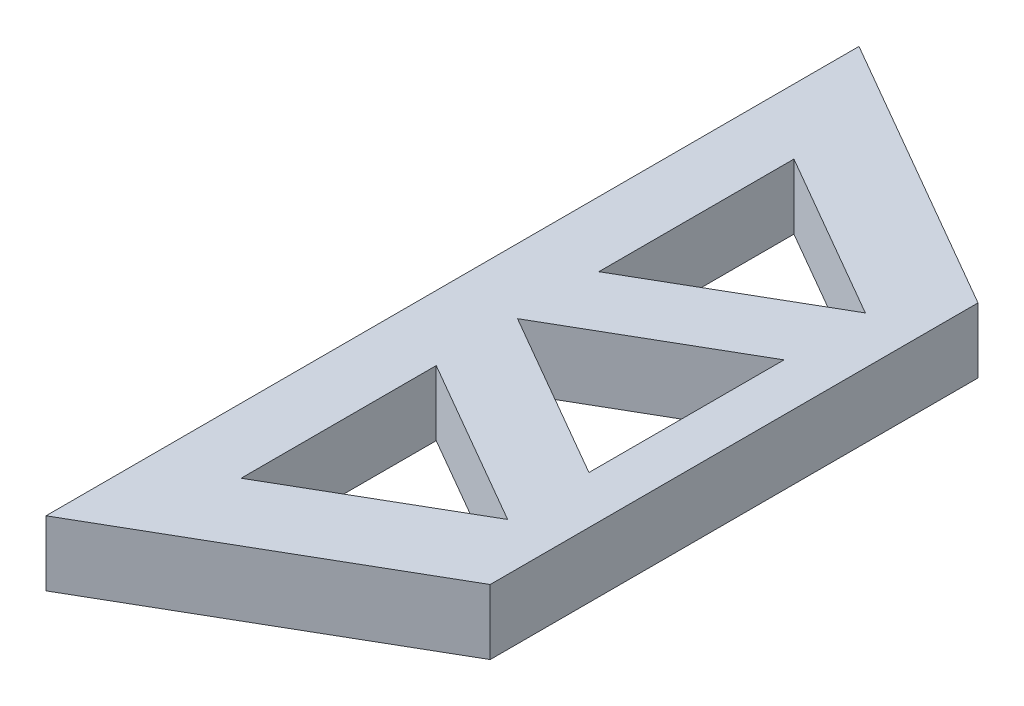
SolidWorks part; units mm, degrees
ref_plane "Front Plane" through (0, 0, 0) normal (0, 0, 1) x (1, 0, 0)
ref_plane "Top Plane" through (0, 0, 0) normal (0, 1, 0) x (1, 0, 0)
ref_plane "Right Plane" through (0, 0, 0) normal (1, 0, 0) x (0, 0, -1)
sketch "Sketch1" plane through (0, 0, 0) normal (0, 1, 0) x (1, 0, 0)
  line L0 (0, 125) -> (0, -125)
  line L1 (0, 125) -> (86.6025, 75)
  line L2 (0, -125) -> (86.6025, -75)
  line L3 (86.6025, 75) -> (86.6025, -75)
  line L4 (20, -85) -> (20, -25)
  line L5 (20, 25) -> (20, 85)
  line L6 (20, -85) -> (71.9615, -55)
  line L8 (20, 85) -> (71.9615, 55)
  line L10 (20, -25) -> (20, 25) construction
  line L17 (20, 25) -> (71.9615, 55)
  line L18 (20, -25) -> (71.9615, -55)
  line L19 (20, 0) -> (71.9615, 30)
  line L20 (71.9615, 30) -> (71.9615, -30)
  line L21 (71.9615, -30) -> (20, 0)
  point P4 (0, 0)
  dimension "D1" = 250
  dimension "D2" = 60
  dimension "D3" = 60
  dimension "D4" = 150
  dimension "D5" = 20
  dimension "D6" = 60
  dimension "D7" = 40
  dimension "D8" = 60
  dimension "D9" = 60
  dimension "D10" = 40
  dimension "D11" = 60
  dimension "D12" = 60
  dimension "D13" = 20
  dimension "D14" = 60
  dimension "D15" = 60
  dimension "D16" = 60
extrude "Boss-Extrude1" add sketch "Sketch1" along normal blind 20
